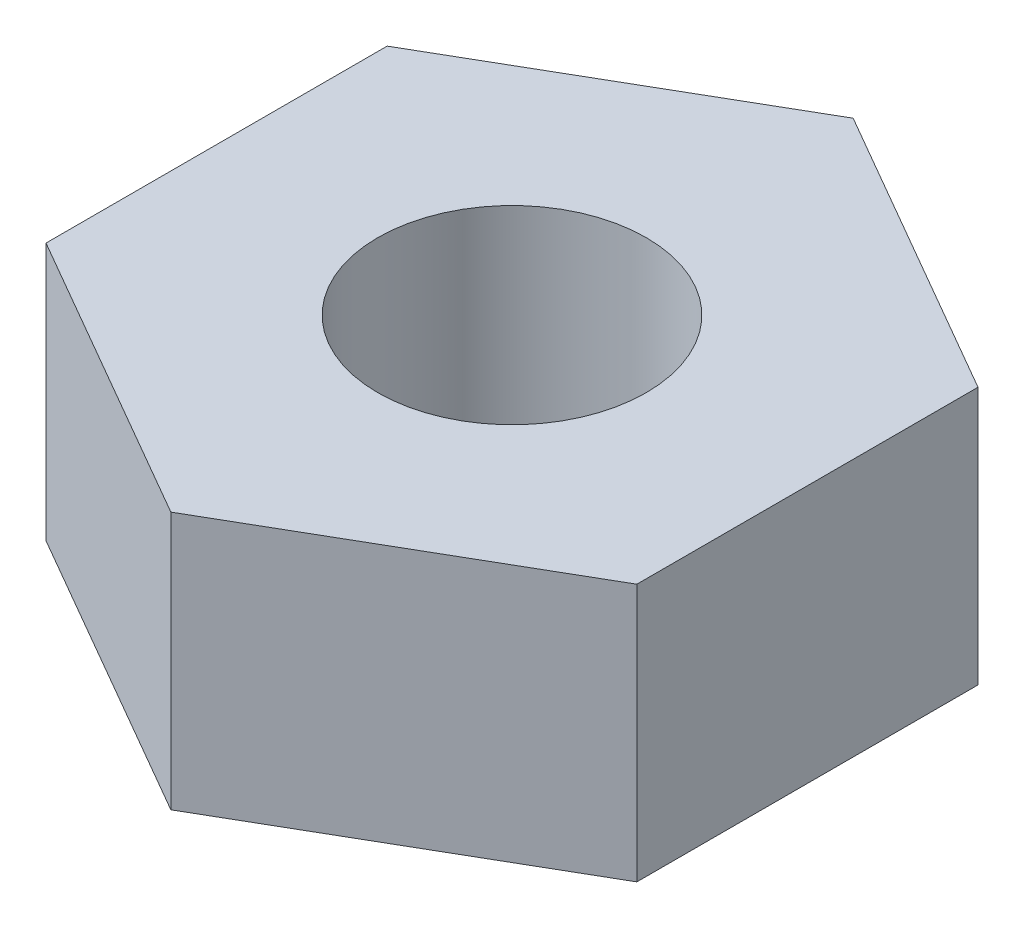
SolidWorks part; units mm, degrees
ref_plane "前视基准面" through (0, 0, 0) normal (0, 0, 1) x (1, 0, 0)
ref_plane "上视基准面" through (0, 0, 0) normal (0, 1, 0) x (1, 0, 0)
ref_plane "右视基准面" through (0, 0, 0) normal (1, 0, 0) x (0, 0, -1)
sketch "草图1" plane through (0, 0, 0) normal (0, 1, 0) x (1, 0, 0)
  line L1 (2.75, -1.5877) -> (2.75, 1.5877)
  line L2 (2.75, 1.5877) -> (0, 3.1754)
  line L3 (0, 3.1754) -> (-2.75, 1.5877)
  line L4 (-2.75, 1.5877) -> (-2.75, -1.5877)
  line L5 (-2.75, -1.5877) -> (0, -3.1754)
  line L6 (0, -3.1754) -> (2.75, -1.5877)
  circle A0 centre (0, 0) radius 2.75 construction
  dimension "D1" = 5.5
extrude "凸台-拉伸1" add sketch "草图1" along normal blind 2.4
sketch "草图4" plane through (0, 0, 0) normal (0, -1, 0) x (1, 0, 0)
  point P0 (0, 0)
hole_wizard "M3 螺纹孔1" positions "3D草图2" profile "草图5" tap size "M3" standard "GB" end condition through all
sketch3d "3D草图2"
  point P0 (0, 0, 0)
  point P3 (0, 0, 0)
sketch "草图5" plane through (0, 0, 0) normal (1, 0, 0) x (0, 0, -1)
  line L0 (0, 0) -> (0, 2.4)
  line L1 (0, 2.4) -> (1.25, 2.4)
  line L2 (1.25, 2.4) -> (1.25, 0)
  line L5 (1.25, 0) -> (0, 0)
  line L11 (0, -6.35) -> (0, 107.95) construction
  dimension "通孔螺纹孔钻头直径" = 2.5
  dimension "通孔螺纹孔钻头深度" = 2.4
cosmetic thread "孔螺蚊线1"
cosmetic thread "孔螺蚊线2"
